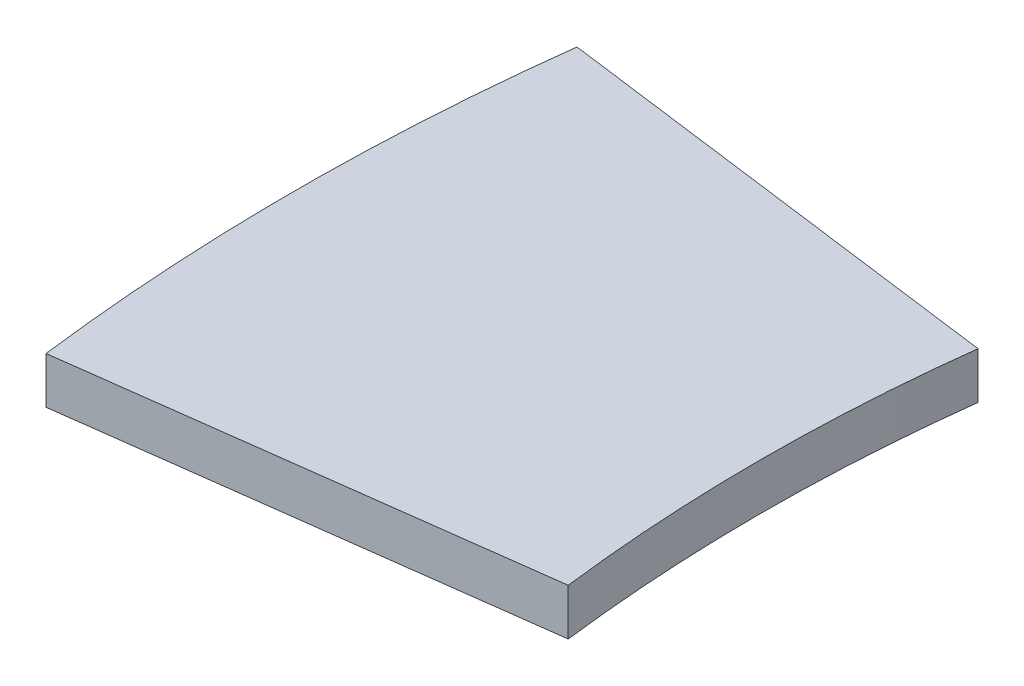
SolidWorks part; units mm, degrees
material "NdFeB"
ref_plane "Front Plane" through (0, 0, 0) normal (0, 0, 1) x (1, 0, 0)
ref_plane "Top Plane" through (0, 0, 0) normal (0, 1, 0) x (1, 0, 0)
ref_plane "Right Plane" through (0, 0, 0) normal (1, 0, 0) x (0, 0, -1)
sketch "Sketch1" plane through (0, 0, 0) normal (0, 1, 0) x (1, 0, 0)
  line L0 (-46.6262, 55) -> (52.5227, 41.9468) construction
  line L1 (-46.6262, -55) -> (52.5227, -41.9468) construction
  line L2 (50, 0) -> (-50, 0) construction
  line L3 (-47.9814, 57.1436) -> (51.1658, 44.0906)
  line L4 (-47.9916, -56.8564) -> (51.1658, -43.8847)
  arc A0 (-46.6262, -55) -> (-46.6262, 55) centre (400, 0) cw construction
  arc A1 (52.5227, -41.9468) -> (52.5227, 41.9468) centre (400, 0) cw construction
  arc A2 (-47.9916, -56.8564) -> (-47.9814, 57.1436) centre (408.4683, 0.103) cw
  arc A3 (51.1658, -43.8847) -> (51.1658, 44.0906) centre (408.4683, 0.103) cw
  point P7 (0, 0)
  dimension "D1" = 360
  dimension "D2" = 460
  dimension "D3" = 100.0045
  dimension "D4" = 15
  dimension "D5" = 7.5
  dimension "D6" = 83.8936
  dimension "D7" = 7.5
  dimension "D8" = 100.0028
  dimension "D9" = 51.1658
  dimension "D10" = 114
extrude "Boss-Extrude1" add sketch "Sketch1" along normal mid plane 10
